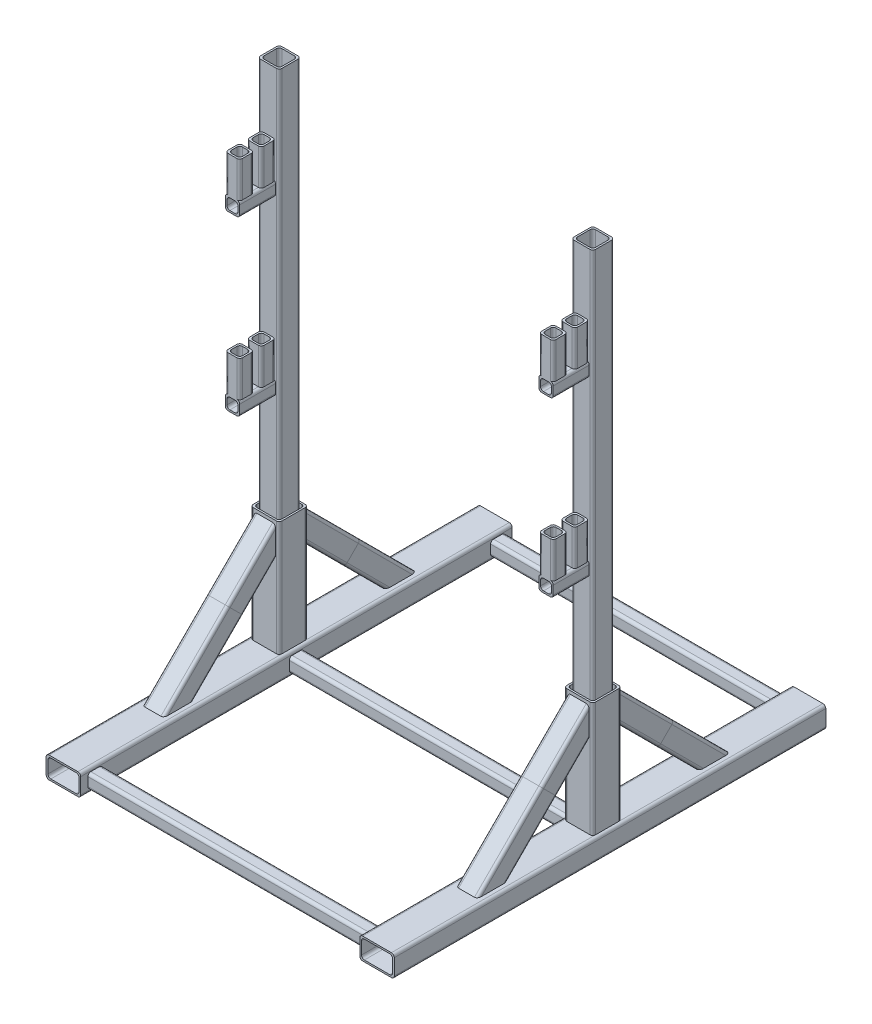
SolidWorks part; units mm, degrees
ref_plane "Front Plane" through (0, 0, 0) normal (0, 0, 1) x (1, 0, 0)
ref_plane "Top Plane" through (0, 0, 0) normal (0, 1, 0) x (1, 0, 0)
ref_plane "Right Plane" through (0, 0, 0) normal (1, 0, 0) x (0, 0, -1)
sketch "Sketch2" plane through (0, 0, 0) normal (0, 1, 0) x (1, 0, 0)
  line L1 (-565, 37.5) -> (-510, 37.5)
  line L2 (-575, 27.5) -> (-575, -27.5)
  line L3 (-565, -37.5) -> (-510, -37.5)
  line L4 (-500, 27.5) -> (-500, -27.5)
  line L5 (-575, 37.5) -> (-500, -37.5) construction
  line L6 (-575, -37.5) -> (-500, 37.5) construction
  line L7 (-559, 31.5) -> (-516, 31.5)
  line L8 (-569, 21.5) -> (-569, -21.5)
  line L9 (-559, -31.5) -> (-516, -31.5)
  line L10 (-506, 21.5) -> (-506, -21.5)
  line L11 (-569, 31.5) -> (-506, -31.5) construction
  line L12 (-569, -31.5) -> (-506, 31.5) construction
  arc A0 (-575, -27.5) -> (-565, -37.5) centre (-565, -27.5) ccw
  arc A1 (-569, -21.5) -> (-559, -31.5) centre (-559, -21.5) ccw
  arc A2 (-516, -31.5) -> (-506, -21.5) centre (-516, -21.5) ccw
  arc A3 (-510, -37.5) -> (-500, -27.5) centre (-510, -27.5) ccw
  arc A4 (-516, 31.5) -> (-506, 21.5) centre (-516, 21.5) cw
  arc A5 (-510, 37.5) -> (-500, 27.5) centre (-510, 27.5) cw
  arc A6 (-559, 31.5) -> (-569, 21.5) centre (-559, 21.5) ccw
  arc A7 (-565, 37.5) -> (-575, 27.5) centre (-565, 27.5) ccw
  point P0 (-537.5, 0)
  point P5 (-537.5, 0)
  dimension "D6" = 10
  dimension "D1" = 75
  dimension "D2" = 75
  dimension "D3" = 6
  dimension "D4" = 0
  dimension "D5" = 500
extrude "Boss-Extrude1" add sketch "Sketch2" against normal blind 1750
sketch "Sketch3" plane through (0, 0, 37.5) normal (0, 0, 1) x (1, 0, 0)
  line L0 (-500, -1750) -> (-500, 0) construction
  line L1 (-546.5, -346) -> (-528.5, -346)
  line L2 (-556.5, -356) -> (-556.5, -374)
  line L3 (-546.5, -384) -> (-528.5, -384)
  line L4 (-518.5, -356) -> (-518.5, -374)
  line L5 (-556.5, -346) -> (-518.5, -384) construction
  line L6 (-556.5, -384) -> (-518.5, -346) construction
  line L7 (-552.5, -340) -> (-522.5, -340)
  line L8 (-562.5, -350) -> (-562.5, -380)
  line L9 (-552.5, -390) -> (-522.5, -390)
  line L10 (-512.5, -350) -> (-512.5, -380)
  line L11 (-562.5, -340) -> (-512.5, -390) construction
  line L12 (-562.5, -390) -> (-512.5, -340) construction
  line L13 (41.25, 0) -> (-41.25, 0) construction
  arc A0 (-556.5, -374) -> (-546.5, -384) centre (-546.5, -374) ccw
  arc A1 (-562.5, -380) -> (-552.5, -390) centre (-552.5, -380) ccw
  arc A2 (-522.5, -390) -> (-512.5, -380) centre (-522.5, -380) ccw
  arc A3 (-528.5, -384) -> (-518.5, -374) centre (-528.5, -374) ccw
  arc A4 (-528.5, -346) -> (-518.5, -356) centre (-528.5, -356) cw
  arc A5 (-522.5, -340) -> (-512.5, -350) centre (-522.5, -350) cw
  arc A6 (-546.5, -346) -> (-556.5, -356) centre (-546.5, -356) ccw
  arc A7 (-552.5, -340) -> (-562.5, -350) centre (-552.5, -350) ccw
  point P0 (-537.5, -365)
  point P5 (-537.5, -365)
  dimension "D6" = 10
  dimension "D1" = 50
  dimension "D2" = 50
  dimension "D3" = 6
  dimension "D4" = 37.5
  dimension "D5" = 340
extrude "Boss-Extrude2" add sketch "Sketch3" along normal blind 125
sketch "Sketch4" plane through (0, -340, 0) normal (0, 1, 0) x (1, 0, 0)
  line L0 (-546.5, -43.5) -> (-528.5, -43.5)
  line L1 (-556.5, -53.5) -> (-556.5, -71.5)
  line L2 (-546.5, -81.5) -> (-528.5, -81.5)
  line L3 (-518.5, -53.5) -> (-518.5, -71.5)
  line L4 (-556.5, -43.5) -> (-518.5, -81.5) construction
  line L5 (-556.5, -81.5) -> (-518.5, -43.5) construction
  line L6 (-552.5, -37.5) -> (-522.5, -37.5)
  line L7 (-562.5, -47.5) -> (-562.5, -77.5)
  line L8 (-552.5, -87.5) -> (-522.5, -87.5)
  line L9 (-512.5, -47.5) -> (-512.5, -77.5)
  line L10 (-562.5, -37.5) -> (-512.5, -87.5) construction
  line L11 (-562.5, -87.5) -> (-512.5, -37.5) construction
  line L12 (-522.5, -37.5) -> (-552.5, -37.5) construction
  line L13 (-512.5, -162.5) -> (-512.5, -37.5) construction
  line L14 (-546.5, -118.5) -> (-528.5, -118.5)
  line L15 (-556.5, -128.5) -> (-556.5, -146.5)
  line L16 (-546.5, -156.5) -> (-528.5, -156.5)
  line L17 (-518.5, -128.5) -> (-518.5, -146.5)
  line L18 (-556.5, -118.5) -> (-518.5, -156.5) construction
  line L19 (-556.5, -156.5) -> (-518.5, -118.5) construction
  line L20 (-552.5, -112.5) -> (-522.5, -112.5)
  line L21 (-562.5, -122.5) -> (-562.5, -152.5)
  line L22 (-552.5, -162.5) -> (-522.5, -162.5)
  line L23 (-512.5, -122.5) -> (-512.5, -152.5)
  line L24 (-562.5, -112.5) -> (-512.5, -162.5) construction
  line L25 (-562.5, -162.5) -> (-512.5, -112.5) construction
  line L26 (-522.5, -162.5) -> (-552.5, -162.5) construction
  arc A0 (-556.5, -71.5) -> (-546.5, -81.5) centre (-546.5, -71.5) ccw
  arc A1 (-562.5, -77.5) -> (-552.5, -87.5) centre (-552.5, -77.5) ccw
  arc A2 (-522.5, -87.5) -> (-512.5, -77.5) centre (-522.5, -77.5) ccw
  arc A3 (-528.5, -81.5) -> (-518.5, -71.5) centre (-528.5, -71.5) ccw
  arc A4 (-528.5, -43.5) -> (-518.5, -53.5) centre (-528.5, -53.5) cw
  arc A5 (-522.5, -37.5) -> (-512.5, -47.5) centre (-522.5, -47.5) cw
  arc A6 (-546.5, -43.5) -> (-556.5, -53.5) centre (-546.5, -53.5) ccw
  arc A7 (-552.5, -37.5) -> (-562.5, -47.5) centre (-552.5, -47.5) ccw
  arc A8 (-556.5, -146.5) -> (-546.5, -156.5) centre (-546.5, -146.5) ccw
  arc A9 (-562.5, -152.5) -> (-552.5, -162.5) centre (-552.5, -152.5) ccw
  arc A10 (-522.5, -162.5) -> (-512.5, -152.5) centre (-522.5, -152.5) ccw
  arc A11 (-528.5, -156.5) -> (-518.5, -146.5) centre (-528.5, -146.5) ccw
  arc A12 (-528.5, -118.5) -> (-518.5, -128.5) centre (-528.5, -128.5) cw
  arc A13 (-522.5, -112.5) -> (-512.5, -122.5) centre (-522.5, -122.5) cw
  arc A14 (-546.5, -118.5) -> (-556.5, -128.5) centre (-546.5, -128.5) ccw
  arc A15 (-552.5, -112.5) -> (-562.5, -122.5) centre (-552.5, -122.5) ccw
  point P0 (-537.5, -62.5)
  point P5 (-537.5, -62.5)
  point P38 (-537.5, -137.5)
  point P43 (-537.5, -137.5)
  dimension "D4" = 10
  dimension "D9" = 10
  dimension "D1" = 50
  dimension "D2" = 50
  dimension "D3" = 6
  dimension "D5" = 0
  dimension "D6" = 25
  dimension "D7" = 50
  dimension "D8" = 50
  dimension "D10" = 0
  dimension "D11" = 25
  dimension "D12" = 6
extrude "Boss-Extrude3" add sketch "Sketch4" along normal blind 125
pattern_linear "LPattern1" count 2 spacing 600 along (0, -1, 0) of "Boss-Extrude2", "Boss-Extrude3"
sketch "Sketch5" plane through (0, -1750, 0) normal (0, -1, 0) x (1, 0, 0)
  line L0 (-500, 27.5) -> (-500, -27.5) construction
  line L1 (-577.5, 50) -> (-497.5, 50)
  line L2 (-587.5, 40) -> (-587.5, -40)
  line L3 (-577.5, -50) -> (-497.5, -50)
  line L4 (-487.5, 40) -> (-487.5, -40)
  line L5 (-587.5, 50) -> (-487.5, -50) construction
  line L6 (-587.5, -50) -> (-487.5, 50) construction
  line L7 (-571.5, 44) -> (-503.5, 44)
  line L8 (-581.5, 34) -> (-581.5, -34)
  line L9 (-571.5, -44) -> (-503.5, -44)
  line L10 (-493.5, 34) -> (-493.5, -34)
  line L11 (-581.5, 44) -> (-493.5, -44) construction
  line L12 (-581.5, -44) -> (-493.5, 44) construction
  line L13 (-510, -37.5) -> (-565, -37.5) construction
  arc A0 (-497.5, -50) -> (-487.5, -40) centre (-497.5, -40) ccw
  arc A1 (-503.5, -44) -> (-493.5, -34) centre (-503.5, -34) ccw
  arc A2 (-587.5, -40) -> (-577.5, -50) centre (-577.5, -40) ccw
  arc A3 (-581.5, -34) -> (-571.5, -44) centre (-571.5, -34) ccw
  arc A4 (-571.5, 44) -> (-581.5, 34) centre (-571.5, 34) ccw
  arc A5 (-577.5, 50) -> (-587.5, 40) centre (-577.5, 40) ccw
  arc A6 (-503.5, 44) -> (-493.5, 34) centre (-503.5, 34) cw
  arc A7 (-497.5, 50) -> (-487.5, 40) centre (-497.5, 40) cw
  point P0 (-537.5, 0)
  point P5 (-537.5, 0)
  dimension "D6" = 10
  dimension "D1" = 100
  dimension "D2" = 100
  dimension "D3" = 6
  dimension "D4" = 37.5
  dimension "D5" = 37.5
extrude "Boss-Extrude4" add sketch "Sketch5" against normal blind 400 separate body
sketch "Sketch6" plane through (0, 0, 0) normal (0, 0, 1) x (1, 0, 0)
  line L0 (-497.5, -1750) -> (-577.5, -1750) construction
  line L1 (-587.5, -1750) -> (-487.5, -1750)
  line L2 (-597.5, -1760) -> (-597.5, -1815)
  line L3 (-587.5, -1825) -> (-487.5, -1825)
  line L4 (-477.5, -1760) -> (-477.5, -1815)
  line L5 (-597.5, -1750) -> (-477.5, -1825) construction
  line L6 (-597.5, -1825) -> (-477.5, -1750) construction
  line L7 (-581.5, -1756) -> (-493.5, -1756)
  line L8 (-591.5, -1766) -> (-591.5, -1809)
  line L9 (-581.5, -1819) -> (-493.5, -1819)
  line L10 (-483.5, -1766) -> (-483.5, -1809)
  line L11 (-591.5, -1756) -> (-483.5, -1819) construction
  line L12 (-591.5, -1819) -> (-483.5, -1756) construction
  line L13 (-487.5, -1350) -> (-487.5, -1750) construction
  arc A0 (-597.5, -1815) -> (-587.5, -1825) centre (-587.5, -1815) ccw
  arc A1 (-591.5, -1809) -> (-581.5, -1819) centre (-581.5, -1809) ccw
  arc A2 (-487.5, -1825) -> (-477.5, -1815) centre (-487.5, -1815) ccw
  arc A3 (-493.5, -1819) -> (-483.5, -1809) centre (-493.5, -1809) ccw
  arc A4 (-493.5, -1756) -> (-483.5, -1766) centre (-493.5, -1766) cw
  arc A5 (-487.5, -1750) -> (-477.5, -1760) centre (-487.5, -1760) cw
  arc A6 (-581.5, -1756) -> (-591.5, -1766) centre (-581.5, -1766) ccw
  arc A7 (-587.5, -1750) -> (-597.5, -1760) centre (-587.5, -1760) ccw
  point P0 (-537.5, -1787.5)
  point P5 (-537.5, -1787.5)
  dimension "D7" = 10
  dimension "D1" = 120
  dimension "D2" = 75
  dimension "D3" = 6
  dimension "D4" = 6
  dimension "D5" = 0
  dimension "D6" = 50
extrude "Boss-Extrude5" add sketch "Sketch6" along normal blind 750
sketch "Sketch8" plane through (0, 0, 0) normal (1, 0, 0) x (0, 0, -1)
  line L0 (0, -1741.6897) -> (-332.5605, -1409.1293)
  line L1 (0, -1741.6897) -> (-380.9042, -1741.6897)
  dimension "D1" = 45
ref_plane "Plane1" through (0, -870.8449, 870.8449) normal (0, 0.7071, -0.7071) x (0, 0.7071, 0.7071)
sketch "Sketch9" plane through (0, -870.8449, 870.8449) normal (0, 0.7071, -0.7071) x (0, 0.7071, 0.7071)
  line L0 (-1217.9914, -575) -> (19.4454, -575) construction
  line L1 (-937.0815, -575) -> (-992.0815, -575)
  line L2 (-927.0815, -565) -> (-927.0815, -510)
  line L3 (-937.0815, -500) -> (-992.0815, -500)
  line L4 (-1002.0815, -565) -> (-1002.0815, -510)
  line L5 (-927.0815, -575) -> (-1002.0815, -500) construction
  line L6 (-927.0815, -500) -> (-1002.0815, -575) construction
  line L7 (-943.0815, -569) -> (-986.0815, -569)
  line L8 (-933.0815, -559) -> (-933.0815, -516)
  line L9 (-943.0815, -506) -> (-986.0815, -506)
  line L10 (-996.0815, -559) -> (-996.0815, -516)
  line L11 (-933.0815, -569) -> (-996.0815, -506) construction
  line L12 (-933.0815, -506) -> (-996.0815, -569) construction
  line L16 (-1202.0815, -497.5) -> (-1202.0815, -577.5) construction
  arc A0 (-933.0815, -516) -> (-943.0815, -506) centre (-943.0815, -516) ccw
  arc A1 (-927.0815, -510) -> (-937.0815, -500) centre (-937.0815, -510) ccw
  arc A2 (-992.0815, -500) -> (-1002.0815, -510) centre (-992.0815, -510) ccw
  arc A3 (-986.0815, -506) -> (-996.0815, -516) centre (-986.0815, -516) ccw
  arc A4 (-992.0815, -575) -> (-1002.0815, -565) centre (-992.0815, -565) cw
  arc A5 (-986.0815, -569) -> (-996.0815, -559) centre (-986.0815, -559) cw
  arc A6 (-943.0815, -569) -> (-933.0815, -559) centre (-943.0815, -559) ccw
  arc A7 (-937.0815, -575) -> (-927.0815, -565) centre (-937.0815, -565) ccw
  point P0 (-964.5815, -537.5)
  point P5 (-964.5815, -537.5)
  dimension "D4" = 10
  dimension "D1" = 75
  dimension "D2" = 75
  dimension "D3" = 6
  dimension "D5" = 0
  dimension "D6" = 200
mirror "Mirror1" about plane through (0, 0, 0) normal (0, 0, 1) of "Boss-Extrude5"
sketch "Sketch10" plane through (-477.5, 0, 0) normal (1, 0, 0) x (0, 0, -1)
  line L0 (0, 66) -> (0, -66) construction
  line L1 (-709, -1768.5) -> (-691, -1768.5)
  line L2 (-719, -1778.5) -> (-719, -1796.5)
  line L3 (-709, -1806.5) -> (-691, -1806.5)
  line L4 (-681, -1778.5) -> (-681, -1796.5)
  line L5 (-719, -1768.5) -> (-681, -1806.5) construction
  line L6 (-719, -1806.5) -> (-681, -1768.5) construction
  line L7 (-715, -1762.5) -> (-685, -1762.5)
  line L8 (-725, -1772.5) -> (-725, -1802.5)
  line L9 (-715, -1812.5) -> (-685, -1812.5)
  line L10 (-675, -1772.5) -> (-675, -1802.5)
  line L11 (-725, -1762.5) -> (-675, -1812.5) construction
  line L12 (-725, -1812.5) -> (-675, -1762.5) construction
  line L13 (40, -1750) -> (-40, -1750) construction
  arc A0 (-685, -1762.5) -> (-675, -1772.5) centre (-685, -1772.5) cw
  arc A1 (-691, -1768.5) -> (-681, -1778.5) centre (-691, -1778.5) cw
  arc A2 (-691, -1806.5) -> (-681, -1796.5) centre (-691, -1796.5) ccw
  arc A3 (-685, -1812.5) -> (-675, -1802.5) centre (-685, -1802.5) ccw
  arc A4 (-725, -1802.5) -> (-715, -1812.5) centre (-715, -1802.5) ccw
  arc A5 (-719, -1796.5) -> (-709, -1806.5) centre (-709, -1796.5) ccw
  arc A6 (-709, -1768.5) -> (-719, -1778.5) centre (-709, -1778.5) ccw
  arc A7 (-715, -1762.5) -> (-725, -1772.5) centre (-715, -1772.5) ccw
  point P0 (-700, -1787.5)
  point P5 (-700, -1787.5)
  dimension "D6" = 10
  dimension "D1" = 50
  dimension "D2" = 50
  dimension "D3" = 6
  dimension "D4" = 700
  dimension "D5" = 37.5
extrude "Boss-Extrude7" add sketch "Sketch10" along normal blind 485
ref_plane "Plane2" through (0, 0, 50) normal (0, 0, 1) x (1, 0, 0)
extrude "Boss-Extrude8" add sketch "Sketch9" along normal up to surface (227.7684 mm away) up to plane "Plane2"
surface "Surface-Extrude5" sketch "Sketch8"
ref_plane "Plane3" through (0, -900, -900) normal (0, 0.7071, 0.7071) x (1, 0, 0)
sketch "Sketch12" plane through (0, -900, -900) normal (0, 0.7071, 0.7071) x (1, 0, 0)
  line L0 (-510, -1002.0815) -> (-565, -1002.0815)
  line L1 (-500, -992.0815) -> (-500, -937.0815)
  line L2 (-510, -927.0815) -> (-565, -927.0815)
  line L3 (-575, -992.0815) -> (-575, -937.0815)
  line L4 (-500, -1002.0815) -> (-575, -927.0815) construction
  line L5 (-500, -927.0815) -> (-575, -1002.0815) construction
  line L6 (-516, -996.0815) -> (-559, -996.0815)
  line L7 (-506, -986.0815) -> (-506, -943.0815)
  line L8 (-516, -933.0815) -> (-559, -933.0815)
  line L9 (-569, -986.0815) -> (-569, -943.0815)
  line L10 (-506, -996.0815) -> (-569, -933.0815) construction
  line L11 (-506, -933.0815) -> (-569, -996.0815) construction
  line L12 (-487.5, -926.3099) -> (-487.5, -1209.1526) construction
  line L17 (-577.5, -1202.0815) -> (-497.5, -1202.0815) construction
  arc A0 (-506, -943.0815) -> (-516, -933.0815) centre (-516, -943.0815) ccw
  arc A1 (-500, -937.0815) -> (-510, -927.0815) centre (-510, -937.0815) ccw
  arc A2 (-565, -927.0815) -> (-575, -937.0815) centre (-565, -937.0815) ccw
  arc A3 (-559, -933.0815) -> (-569, -943.0815) centre (-559, -943.0815) ccw
  arc A4 (-565, -1002.0815) -> (-575, -992.0815) centre (-565, -992.0815) cw
  arc A5 (-559, -996.0815) -> (-569, -986.0815) centre (-559, -986.0815) cw
  arc A6 (-516, -996.0815) -> (-506, -986.0815) centre (-516, -986.0815) ccw
  arc A7 (-510, -1002.0815) -> (-500, -992.0815) centre (-510, -992.0815) ccw
  point P0 (-537.5, -964.5815)
  point P5 (-537.5, -964.5815)
  dimension "D4" = 10
  dimension "D1" = 75
  dimension "D2" = 75
  dimension "D3" = 6
  dimension "D5" = 50
  dimension "D6" = 200
extrude "Boss-Extrude9" add sketch "Sketch12" along normal up to surface (216 mm away)
surface "Surface-Extrude6"
pattern_linear "LPattern2" count 3 spacing 700 along (0, 0, -1) of "Boss-Extrude7"
mirror "Mirror5" about plane through (7.5, -1772.5, 685) normal (-1, 0, 0) of bodies 129
surface "Surface-Extrude7"
surface "Surface-Extrude8"
